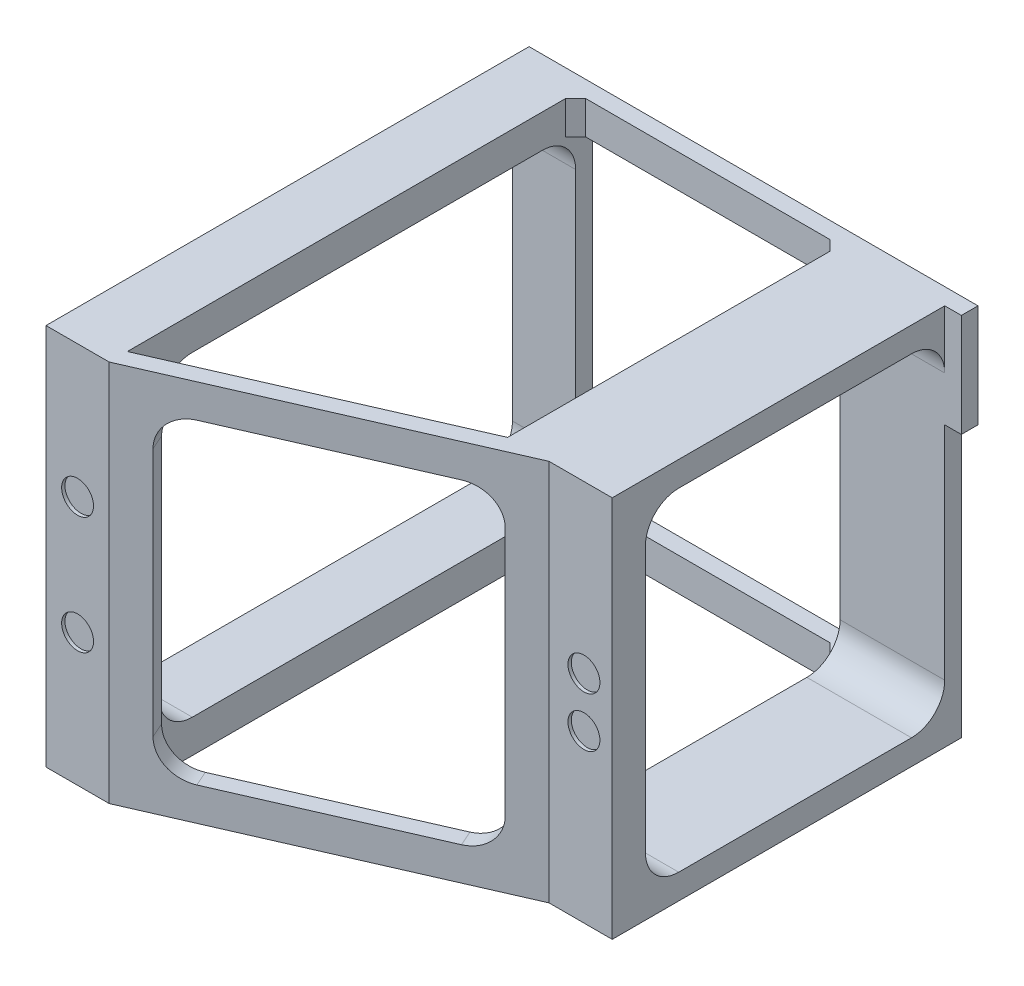
SolidWorks part; units mm, degrees
ref_plane "Front Plane" through (0, 0, 0) normal (1, 0, 0) x (0, 1, 0)
ref_plane "Top Plane" through (0, 0, 0) normal (0, 0, 1) x (0, 1, 0)
ref_plane "Right Plane" through (0, 0, 0) normal (0, 1, 0) x (-1, 0, 0)
sketch "Sketch2" plane through (0, 0, 0) normal (0, 0, 1) x (0, 1, 0)
  line L0 (0, 100.3268) -> (0, -104.3828) construction
  line L1 (0, 0) -> (145.436, 0) construction
  line L2 (-57.5, -65) -> (57.5, -65)
  line L3 (-57.5, -65) -> (-57.5, 65)
  line L4 (-57.5, 65) -> (57.5, 65)
  line L5 (57.5, -65) -> (57.5, 65)
  circle A0 centre (-18.09, -55.5) radius 4.8
  circle A1 centre (18.08, -55.5) radius 4.8
  dimension "D3" = 9.6
  dimension "D4" = 9.6
  dimension "D5" = 39.42
  dimension "D1" = 115
  dimension "D2" = 130
  dimension "D6" = 9.5
  dimension "D7" = 36.17
extrude "Boss-Extrude1" add sketch "Sketch2" along normal blind 5
sketch "Sketch3" plane through (0, 57.5, 0) normal (0, 1, 0) x (-1, 0, 0)
  line L0 (-65, 5) -> (-46, 5)
  line L1 (-65, 5) -> (65, 5) construction
  line L2 (-46, 5) -> (46, 45.27)
  line L3 (46, 45.27) -> (65, 45.27)
  line L4 (65, 45.27) -> (65, 39.812)
  line L6 (46, 39.812) -> (-33.5307, 5)
  line L7 (65, 5) -> (65, 0) construction
  line L8 (46, 39.812) -> (65, 39.812)
  line L9 (-65, 5) -> (-65, 0)
  line L10 (-65, 5) -> (-65, 0) construction
  line L11 (-65, 0) -> (-33.5307, 0)
  line L12 (-65, 0) -> (65, 0) construction
  line L13 (-33.5307, 0) -> (-33.5307, 5)
  dimension "D1" = 19
  dimension "D2" = 19
  dimension "D3" = 40.27
  dimension "D4" = 5
extrude "Boss-Extrude2" add sketch "Sketch3" against normal up to surface (115 mm away) up to face at (0, -57.5, 2.5)
sketch "Sketch4" plane through (0, 0, 5) normal (0, 0, 1) x (1, 0, 0)
  line L0 (33.5307, -57.5) -> (33.5307, 57.5)
  line L1 (-46, 57.5) -> (46, 57.5) construction
  line L2 (33.5307, 57.5) -> (-65, 57.5)
  line L3 (-65, 57.5) -> (-65, -57.5)
  line L4 (-65, -57.5) -> (33.5307, -57.5)
extrude "Cut-Extrude1" cut sketch "Sketch4" against normal blind 5
sketch "Sketch5" plane through (0, 0, 5) normal (0, 0, 1) x (1, 0, 0)
  line L0 (0, 0) -> (99.3947, 0) construction
  line L1 (65, -57.5) -> (65, 57.5) construction
  circle A0 centre (56.5, 7.5) radius 4.8
  circle A1 centre (56.5, -7.5) radius 4.8
  dimension "D2" = 9.6
  dimension "D3" = 9.6
  dimension "D1" = 15
  dimension "D4" = 7.5
  dimension "D5" = 8.5
extrude "Cut-Extrude2" cut sketch "Sketch5" against normal blind 1
sketch "Sketch6" plane through (0, 0, 45.27) normal (0, 0, 1) x (1, 0, 0)
  line L0 (0, 0) -> (90.3346, 0) construction
  line L1 (-65, -57.5) -> (-65, 57.5) construction
  circle A0 centre (-55.5, 17.65) radius 4.8
  circle A1 centre (-55.5, -17.65) radius 4.8
  dimension "D3" = 9.6
  dimension "D4" = 9.6
  dimension "D1" = 35.3
  dimension "D5" = 9.5
extrude "Cut-Extrude4" cut sketch "Sketch6" against normal blind 1
sketch "Sketch7" plane through (0, 0, 39.812) normal (0, 0, -1) x (1, 0, 0)
  line L1 (-65, -57.5) -> (-46, -57.5)
  line L2 (-65, -57.5) -> (-65, 57.5)
  line L3 (-65, 57.5) -> (-46, 57.5)
  line L4 (-46, -57.5) -> (-46, 57.5)
extrude "Boss-Extrude3" add sketch "Sketch7" along normal up to surface (39.812 mm away) up to face at (49.2654, 0, 0)
sketch "Sketch8" plane through (0, 0, 0) normal (0, 0, -1) x (1, 0, 0)
  line L1 (-65, 57.5) -> (-46, 57.5)
  line L2 (-65, 57.5) -> (-65, -57.5)
  line L3 (-65, -57.5) -> (-46, -57.5)
  line L4 (-46, 57.5) -> (-46, -57.5)
  line L5 (33.5307, 57.5) -> (65, 57.5)
  line L6 (33.5307, 57.5) -> (33.5307, -57.5)
  line L7 (33.5307, -57.5) -> (65, -57.5)
  line L8 (65, 57.5) -> (65, -57.5)
extrude "Boss-Extrude4" add sketch "Sketch8" along normal blind 100
sketch "Sketch9" plane through (-65, 0, 0) normal (-1, 0, 0) x (0, -1, 0)
  line L0 (57.5, 45.27) -> (-57.5, 45.27) construction
  line L1 (-37.5, -95) -> (37.5, -95)
  line L2 (-47.5, -85) -> (-47.5, 20.27)
  line L3 (-37.5, 30.27) -> (37.5, 30.27)
  line L4 (47.5, -85) -> (47.5, 20.27)
  line L5 (57.5, -100) -> (-57.5, -100) construction
  line L6 (-57.5, -100) -> (-57.5, 45.27) construction
  line L7 (57.5, 45.27) -> (57.5, -100) construction
  arc A0 (37.5, -95) -> (47.5, -85) centre (37.5, -85) ccw
  arc A1 (-37.5, -95) -> (-47.5, -85) centre (-37.5, -85) cw
  arc A2 (37.5, 30.27) -> (47.5, 20.27) centre (37.5, 20.27) cw
  arc A3 (-47.5, 20.27) -> (-37.5, 30.27) centre (-37.5, 20.27) cw
  dimension "D5" = 10
  dimension "D1" = 15
  dimension "D2" = 5
  dimension "D3" = 10
  dimension "D4" = 10
extrude "Cut-Extrude5" cut sketch "Sketch9" against normal up to surface (19 mm away) up to face at (-46, 0, -30.094)
sketch "Sketch10" plane through (65, 0, 0) normal (1, 0, 0) x (0, 1, 0)
  line L0 (-57.5, 5) -> (57.5, 5) construction
  line L1 (-40, -95) -> (40, -95)
  line L2 (-50, -85) -> (-50, -15)
  line L3 (-40, -5) -> (40, -5)
  line L4 (50, -85) -> (50, -15)
  line L5 (-57.5, 5) -> (-57.5, -100) construction
  line L6 (57.5, 5) -> (57.5, -100) construction
  line L7 (57.5, -100) -> (-57.5, -100) construction
  arc A0 (40, -95) -> (50, -85) centre (40, -85) ccw
  arc A1 (40, -5) -> (50, -15) centre (40, -15) cw
  arc A2 (-40, -95) -> (-50, -85) centre (-40, -85) cw
  arc A3 (-50, -15) -> (-40, -5) centre (-40, -15) cw
  dimension "D5" = 10
  dimension "D1" = 10
  dimension "D2" = 7.5
  dimension "D3" = 7.5
  dimension "D4" = 5
extrude "Cut-Extrude6" cut sketch "Sketch10" against normal up to surface (31.4693 mm away) up to face at (33.5307, 0, -47.5)
sketch "Sketch11" plane through (9.233, 0, 21.0935) normal (0.401, 0, 0.9161) x (0.9161, 0, -0.401)
  line L0 (-60.2925, 57.5) -> (40.1349, 57.5) construction
  line L1 (-40.2925, 47.5) -> (20.1349, 47.5)
  line L2 (-50.2925, 37.5) -> (-50.2925, -37.5)
  line L3 (-40.2925, -47.5) -> (20.1349, -47.5)
  line L4 (30.1349, 37.5) -> (30.1349, -37.5)
  line L5 (40.1349, -57.5) -> (-60.2925, -57.5) construction
  line L6 (40.1349, -57.5) -> (40.1349, 57.5) construction
  line L7 (-60.2925, -57.5) -> (-60.2925, 57.5) construction
  arc A0 (20.1349, -47.5) -> (30.1349, -37.5) centre (20.1349, -37.5) ccw
  arc A1 (-50.2925, -37.5) -> (-40.2925, -47.5) centre (-40.2925, -37.5) ccw
  arc A2 (20.1349, 47.5) -> (30.1349, 37.5) centre (20.1349, 37.5) cw
  arc A3 (-40.2925, 47.5) -> (-50.2925, 37.5) centre (-40.2925, 37.5) ccw
  dimension "D5" = 10
  dimension "D1" = 10
  dimension "D2" = 10
  dimension "D3" = 10
  dimension "D4" = 10
extrude "Cut-Extrude7" cut sketch "Sketch11" against normal up to surface (5 mm away) up to face at (-6.2346, 0, 22.406)
sketch "Sketch12" plane through (-65, 0, 0) normal (-1, 0, 0) x (0, 0, 1)
  line L0 (-95, 37.5) -> (-95, -37.5) construction
  line L1 (-100, 57.5) -> (-95, 57.5)
  line L2 (-100, 57.5) -> (-100, 47.5)
  line L3 (-100, 47.5) -> (-95, 47.5)
  line L4 (-95, 57.5) -> (-95, 47.5)
  line L5 (20.27, 47.5) -> (-85, 47.5) construction
  line L6 (-85, -47.5) -> (20.27, -47.5) construction
  line L7 (-100, -57.5) -> (-95, -57.5)
  line L8 (-100, -57.5) -> (-100, -47.5)
  line L9 (-100, -47.5) -> (-95, -47.5)
  line L10 (-95, -57.5) -> (-95, -47.5)
extrude "Boss-Extrude5" add sketch "Sketch12" against normal blind 100
chamfer "Chamfer1" distance 3 angle 45 4 edges at (-46, 52.5, -95) (33.5307, 52.5, -95) (33.5307, -52.5, -95) (-46, -52.5, -95)
sketch "Sketch13" plane through (65, 0, 0) normal (1, 0, 0) x (0, 0, -1)
  line L0 (95, 26.5) -> (95, 57.5)
  line L1 (95, -40) -> (95, 40) construction
  line L2 (95, 57.5) -> (100, 57.5)
  line L3 (100, 57.5) -> (100, 26.5)
  line L4 (100, 57.5) -> (100, -57.5) construction
  line L5 (100, 26.5) -> (95, 26.5)
  dimension "D1" = 31
extrude "Boss-Extrude6" add sketch "Sketch13" along normal blind 5
